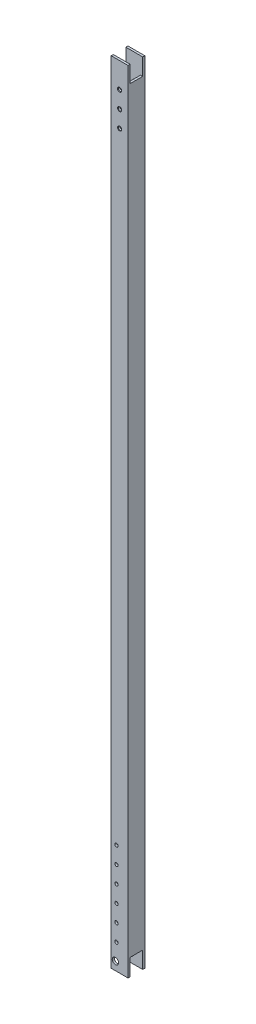
SolidWorks part; units mm, degrees
material "6061 Alloy"
ref_plane "Front" through (0, 0, 0) normal (0, 0, 1) x (1, 0, 0)
ref_plane "Top" through (0, 0, 0) normal (0, 1, 0) x (1, 0, 0)
ref_plane "Right" through (0, 0, 0) normal (1, 0, 0) x (0, 0, -1)
sketch "Sketch1" plane through (0, 0, 0) normal (0, 1, 0) x (1, 0, 0)
  line L1 (-9.525, 9.525) -> (9.525, 9.525)
  line L2 (-9.525, 9.525) -> (-9.525, -9.525)
  line L3 (-9.525, -9.525) -> (9.525, -9.525)
  line L4 (9.525, 9.525) -> (9.525, -9.525)
  line L5 (-9.525, 9.525) -> (9.525, -9.525) construction
  line L6 (-9.525, -9.525) -> (9.525, 9.525) construction
  line L7 (-12.7, 12.7) -> (12.7, 12.7)
  line L8 (-12.7, 12.7) -> (-12.7, -12.7)
  line L9 (-12.7, -12.7) -> (12.7, -12.7)
  line L10 (12.7, 12.7) -> (12.7, -12.7)
  line L11 (-12.7, 12.7) -> (12.7, -12.7) construction
  line L12 (-12.7, -12.7) -> (12.7, 12.7) construction
  point P0 (0, 0)
  point P6 (0, 0)
  dimension "D1" = 3.175
  dimension "D2" = 3.175
  dimension "D3" = 25.4
  dimension "D4" = 25.4
extrude "Boss-Extrude1" add sketch "Sketch1" along normal blind 1143
hole_wizard "#10 Clearance Hole1" positions "Sketch2" profile "Sketch3" hole size "#10" standard "ANSI Inch" end condition through all
sketch "Sketch2" plane through (0, 0, 12.7) normal (0, 0, 1) x (1, 0, 0)
  line L0 (-4.7625, 0) -> (-4.7625, 63.5) construction
  line L1 (-12.7, 0) -> (12.7, 0) construction
  line L2 (-12.7, 1143) -> (-12.7, 0) construction
  line L3 (-4.7625, 63.5) -> (-4.7625, 139.7) construction
  point P2 (-4.7625, 63.5)
  point P9 (-4.7625, 38.1)
  point P11 (-4.7625, 12.7)
  point P22 (-4.7625, 139.7)
  point P25 (-4.7625, 88.9)
  point P32 (-4.7625, 114.3)
  dimension "D1" = 12.7
  dimension "D2" = 25.4
  dimension "D3" = 25.4
  dimension "D4" = 7.9375
  dimension "D5" = 25.4
  dimension "D6" = 25.4
  dimension "D7" = 25.4
sketch "Sketch3" plane through (-4.7625, 114.3, 12.7) normal (1, 0, 0) x (0, -1, 0)
  line L0 (0, 0) -> (0, 25.4)
  line L1 (0, 25.4) -> (2.5527, 25.4)
  line L2 (2.5527, 25.4) -> (2.5527, 0)
  line L5 (2.5527, 0) -> (0, 0)
  line L11 (0, -6.35) -> (0, 107.95) construction
  dimension "Thru Hole Dia." = 5.1054
  dimension "Thru Hole Depth" = 25.4
hole_wizard "#10 Clearance Hole2" positions "Sketch4" profile "Sketch5" hole size "#10" standard "ANSI Inch" end condition through all
sketch "Sketch4" plane through (0, 0, 12.7) normal (0, 0, 1) x (1, 0, 0)
  line L1 (0, 1143) -> (0, 1079.5) construction
  line L2 (-12.7, 1143) -> (12.7, 1143) construction
  line L3 (-12.7, 1143) -> (-12.7, 0) construction
  point P4 (0, 1079.5)
  point P11 (0, 1104.9)
  point P13 (0, 1130.3)
  dimension "D1" = 12.7
  dimension "D2" = 25.4
  dimension "D3" = 25.4
  dimension "D4" = 12.7
sketch "Sketch5" plane through (0, 1130.3, 12.7) normal (1, 0, 0) x (0, -1, 0)
  line L0 (0, 0) -> (0, 25.4)
  line L1 (0, 25.4) -> (3.1877, 25.4)
  line L2 (2.5527, 24.765) -> (2.5527, 0.635)
  line L3 (2.5527, 0.635) -> (3.1877, 0)
  line L5 (3.1877, 0) -> (0, 0)
  line L6 (-2.5527, 0.635) -> (-3.1877, 0) construction
  line L7 (3.1877, 25.4) -> (2.5527, 24.765)
  line L8 (-3.1877, 25.4) -> (-2.5527, 24.765) construction
  line L11 (0, -6.35) -> (0, 107.95) construction
  dimension "Thru Hole Dia." = 5.1054
  dimension "Thru Hole Depth" = 25.4
  dimension "Near C'Sink Dia." = 6.3754
  dimension "Near C'Sink Angle" = 90
  dimension "Far C'Sink Dia." = 6.3754
  dimension "Far C'Sink Angle" = 90
sketch "Sketch6" plane through (0, 1143, 0) normal (0, 1, 0) x (1, 0, 0)
  line L0 (12.7, -12.7) -> (12.7, 12.7) construction
  line L1 (-12.7, 12.7) -> (12.7, 12.7)
  line L2 (-12.7, 12.7) -> (-12.7, 9.525)
  line L3 (-12.7, 9.525) -> (12.7, 9.525)
  line L4 (12.7, 12.7) -> (12.7, 9.525)
  line L5 (-12.7, 12.7) -> (-12.7, -12.7) construction
  line L6 (12.7, -12.7) -> (-12.7, -12.7)
  line L7 (12.7, -12.7) -> (12.7, -9.525)
  line L8 (12.7, -9.525) -> (-12.7, -9.525)
  line L9 (-12.7, -12.7) -> (-12.7, -9.525)
  line L10 (-9.525, -9.525) -> (9.525, -9.525) construction
  line L11 (9.525, 9.525) -> (-9.525, 9.525) construction
extrude "Boss-Extrude2" add sketch "Sketch6" along normal blind 25.4
sketch "Sketch7" plane through (0, 0, 0) normal (0, -1, 0) x (1, 0, 0)
  line L1 (-12.7, -12.7) -> (12.7, -12.7)
  line L2 (-12.7, -12.7) -> (-12.7, -9.525)
  line L3 (-12.7, -9.525) -> (12.7, -9.525)
  line L4 (12.7, -12.7) -> (12.7, -9.525)
  line L5 (-12.7, 12.7) -> (12.7, 12.7)
  line L6 (-12.7, 12.7) -> (-12.7, 9.525)
  line L7 (-12.7, 9.525) -> (12.7, 9.525)
  line L8 (12.7, 12.7) -> (12.7, 9.525)
extrude "Boss-Extrude3" add sketch "Sketch7" along normal blind 25.4
hole_wizard "3/8 (0.375) Diameter Hole2" positions "Sketch8" profile "Sketch9" hole size "3/8" standard "ANSI Inch" end condition through all
sketch "Sketch8" plane through (0, 0, 12.7) normal (0, 0, 1) x (1, 0, 0)
  point P0 (-6.35, -12.7)
sketch "Sketch9" plane through (-6.35, -12.7, 12.7) normal (1, 0, 0) x (0, -1, 0)
  line L0 (0, 0) -> (0, 25.4)
  line L1 (0, 25.4) -> (4.7625, 25.4)
  line L2 (4.7625, 25.4) -> (4.7625, 0)
  line L5 (4.7625, 0) -> (0, 0)
  line L11 (0, -6.35) -> (0, 107.95) construction
  dimension "Thru Hole Dia." = 9.525
  dimension "Thru Hole Depth" = 25.4
